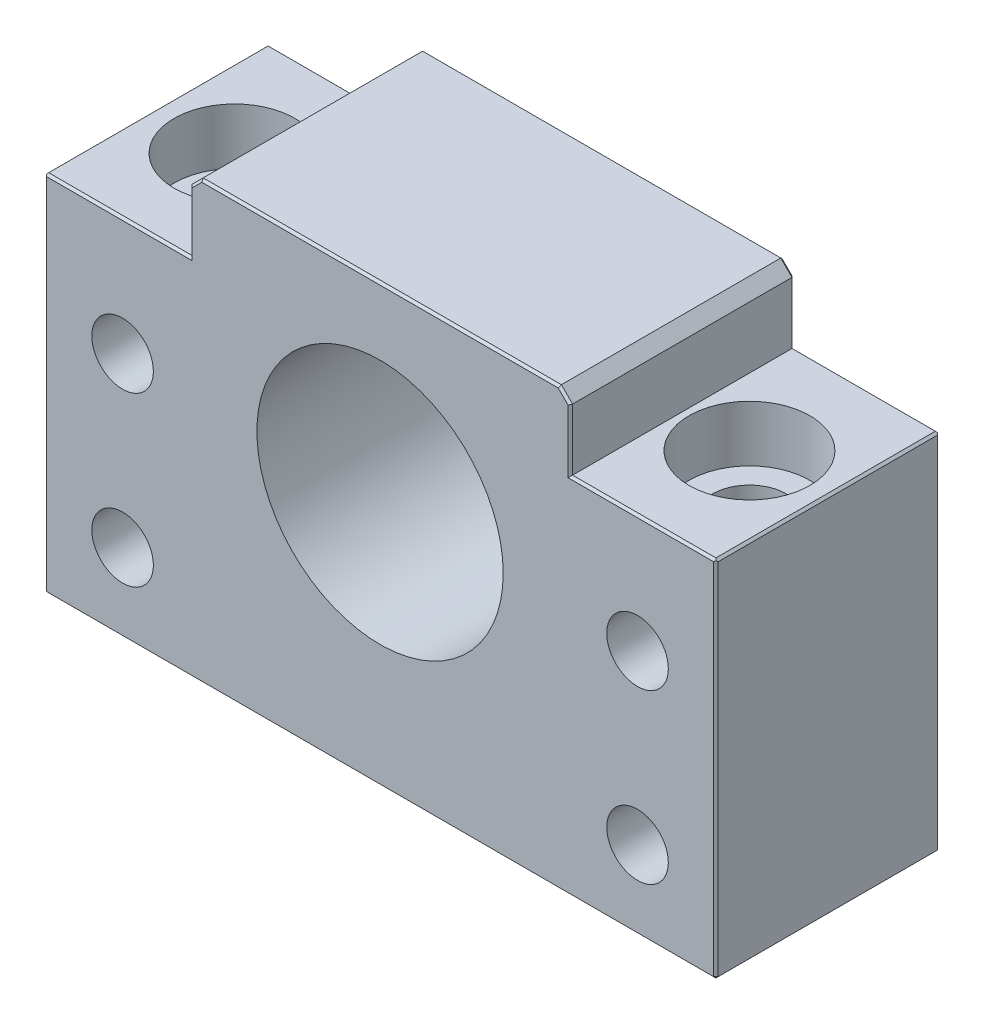
SolidWorks part; units mm, degrees
ref_plane "前视基准面" through (0, 0, 0) normal (0, 0, 1) x (1, 0, 0)
ref_plane "上视基准面" through (0, 0, 0) normal (0, 1, 0) x (1, 0, 0)
ref_plane "右视基准面" through (0, 0, 0) normal (1, 0, 0) x (0, 0, -1)
sketch "草图1" plane through (0, 0, 0) normal (0, 0, 1) x (1, 0, 0)
  line L1 (-30, 16.25) -> (30, 16.25)
  line L2 (-30, 16.25) -> (-30, -16.25)
  line L3 (-30, -16.25) -> (30, -16.25)
  line L4 (30, 16.25) -> (30, -16.25)
  point P0 (0, 0)
  dimension "D1" = 60
  dimension "D2" = 32.5
extrude "凸台-拉伸1" add sketch "草图1" along normal blind 20
sketch "草图2" plane through (0, 16.25, 0) normal (0, 1, 0) x (1, 0, 0)
  line L0 (-17, 0) -> (-17, -20)
  line L1 (30, 0) -> (-30, 0) construction
  line L2 (30, -20) -> (-30, -20) construction
  line L3 (17, -20) -> (17, 0)
  line L4 (30, -20) -> (30, 0) construction
  line L5 (-30, -20) -> (-30, 0) construction
  line L6 (-17, 0) -> (17, 0)
  line L7 (17, -20) -> (-17, -20)
  dimension "D1" = 13
  dimension "D2" = 13
extrude "凸台-拉伸2" add sketch "草图2" along normal blind 6.5
sketch "草图3" plane through (0, 16.25, 0) normal (0, 1, 0) x (1, 0, 0)
  line L0 (-23, 0) -> (-23, -20) construction
  line L1 (-17, 0) -> (-30, 0) construction
  line L2 (-17, -20) -> (-30, -20) construction
  line L3 (-30, -20) -> (-30, 0) construction
  line L4 (23, 0) -> (23, -20) construction
  line L5 (30, 0) -> (17, 0) construction
  line L6 (30, -20) -> (17, -20) construction
  line L7 (30, -20) -> (30, 0) construction
  circle A0 centre (-23, -10) radius 5.4
  circle A1 centre (23, -10) radius 5.4
  dimension "D1" = 7
  dimension "D2" = 7
extrude "切除-拉伸1" cut sketch "草图3" against normal blind 5
sketch "草图4" plane through (0, 11.25, 0) normal (0, 1, 0) x (1, 0, 0)
  circle A0 centre (-23, -10) radius 3.3
  circle A1 centre (23, -10) radius 3.3
extrude "切除-拉伸2" cut sketch "草图4" against normal through all
sketch "草图7" plane through (0, 0, 20) normal (0, 0, 1) x (1, 0, 0)
  line L0 (-23, -16.25) -> (-23, 16.25) construction
  line L1 (-30, -16.25) -> (30, -16.25) construction
  line L2 (-17, 16.25) -> (-30, 16.25) construction
  line L3 (23, 16.25) -> (23, -16.25) construction
  line L4 (30, 16.25) -> (17, 16.25) construction
  line L5 (-30, 16.25) -> (-30, -16.25) construction
  line L6 (30, -16.25) -> (30, 16.25) construction
  circle A0 centre (-23, 5.75) radius 2.75
  circle A1 centre (23, 5.75) radius 2.75
  circle A2 centre (-23, -9.25) radius 2.75
  circle A3 centre (23, -9.25) radius 2.75
  dimension "D3" = 22
  dimension "D5" = 15
  dimension "D1" = 7
  dimension "D2" = 7
  dimension "D4" = 22
  dimension "D6" = 15
extrude "切除-拉伸3" cut sketch "草图7" against normal through all
sketch "草图8" plane through (0, 0, 20) normal (0, 0, 1) x (1, 0, 0)
  line L0 (-23, 5.75) -> (23, 5.75) construction
  circle A0 centre (0, 5.75) radius 11
extrude "切除-拉伸4" cut sketch "草图8" against normal blind 35
chamfer "倒角1" distance 1 angle 45 2 edges at (17, 22.75, 10) (-17, 22.75, 10)
chamfer "倒角2" distance 0.2 angle 45 16 edges at (-16.5, 22.25, 0) (0, 22.75, 0) (16.5, 22.25, 0) (30, 16.25, 10) (16.5, 22.25, 20) (0, 22.75, 20) (-16.5, 22.25, 20) (-30, 16.25, 10)
chamfer "倒角3" distance 0.2 angle 45 8 edges at (-30, -0.1, 0) (-30, -16.25, 10) (-30, -0.1, 20) (0, -16.25, 20) (0, -16.25, 0) (30, -0.1, 0) (30, -16.25, 10) (30, -0.1, 20)
